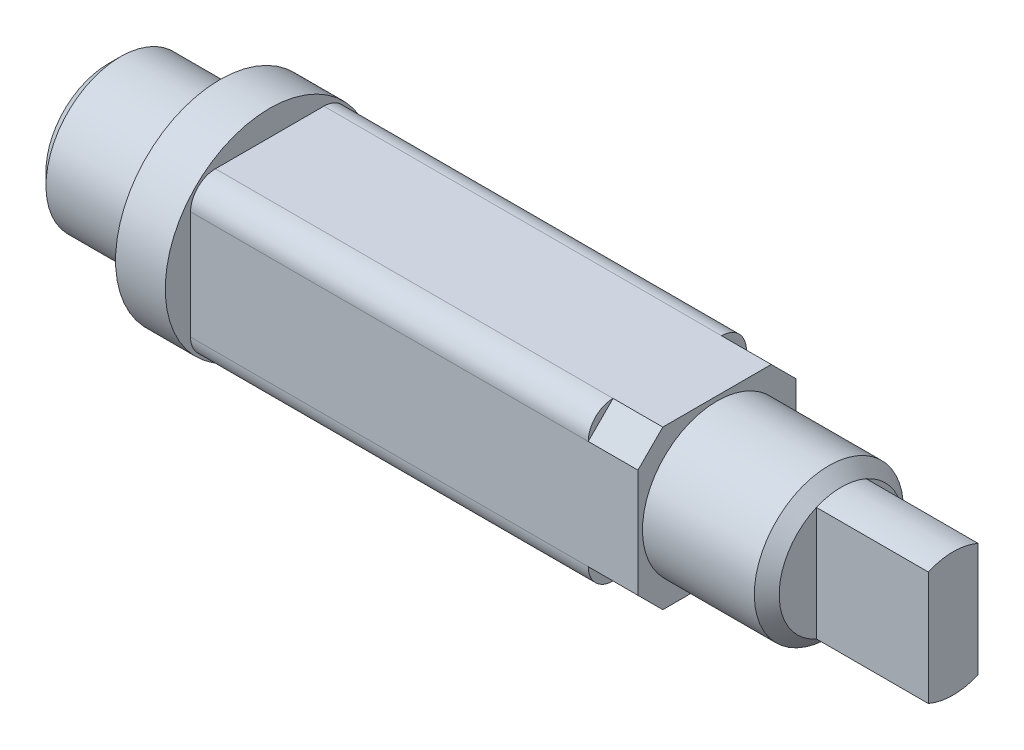
SolidWorks part; units mm, degrees
ref_plane "前视基准面" through (0, 0, 0) normal (0, 0, 1) x (1, 0, 0)
ref_plane "上视基准面" through (0, 0, 0) normal (0, 1, 0) x (1, 0, 0)
ref_plane "右视基准面" through (0, 0, 0) normal (1, 0, 0) x (0, 0, -1)
sketch "草图1" plane through (0, 0, 0) normal (0, 0, 1) x (1, 0, 0)
  line L0 (0, 3) -> (4, 3)
  line L1 (0, 3) -> (-0.5, 2.5)
  line L2 (4, 3) -> (4, 4.2)
  line L3 (4, 4.2) -> (6, 4.2)
  line L4 (6, 4.2) -> (6, 0)
  line L5 (6, 0) -> (0, 0)
  line L8 (-0.5, 2.5) -> (-0.5, 0)
  line L9 (-0.5, 0) -> (0, 0)
  point P10 (-0.5, 3)
revolve "旋转1" add sketch "草图1" angle 360 about L5
ref_plane "基准面1" through (6, 0, 0) normal (1, 0, 0) x (0, 0, -1)
sketch "草图2" plane through (6, 0, 0) normal (1, 0, 0) x (0, 0, -1)
  line L1 (-2.182, 3.182) -> (2.182, 3.182)
  line L2 (-3.182, 2.182) -> (-3.182, -2.182)
  line L3 (-2.182, -3.182) -> (2.182, -3.182)
  line L4 (3.182, 2.182) -> (3.182, -2.182)
  line L5 (-3.182, 3.182) -> (3.182, -3.182) construction
  line L6 (-3.182, -3.182) -> (3.182, 3.182) construction
  arc A0 (3.182, 2.182) -> (2.182, 3.182) centre (2.182, 2.182) ccw
  arc A1 (2.182, -3.182) -> (3.182, -2.182) centre (2.182, -2.182) ccw
  arc A2 (-3.182, -2.182) -> (-2.182, -3.182) centre (-2.182, -2.182) ccw
  arc A3 (-3.182, 2.182) -> (-2.182, 3.182) centre (-2.182, 2.182) cw
  point P0 (0, 0)
  dimension "D1" = 1
extrude "凸台-拉伸1" add sketch "草图2" along normal blind 16
ref_plane "基准面2" through (22, 0, 0) normal (1, 0, 0) x (0, 0, -1)
sketch "草图3" plane through (22, 0, 0) normal (1, 0, 0) x (0, 0, -1)
  line L0 (3.182, 2.182) -> (2.182, 3.182)
  line L1 (2.182, 3.182) -> (-2.182, 3.182)
  line L2 (3.182, 2.182) -> (3.182, -2.182)
  line L3 (2.182, -3.182) -> (-2.182, -3.182)
  line L4 (-3.182, 2.182) -> (-3.182, -2.182)
  line L5 (3.182, 3.182) -> (-3.182, -3.182) construction
  line L6 (3.182, -3.182) -> (-3.182, 3.182) construction
  line L7 (-2.182, 3.182) -> (-3.182, 2.182)
  line L8 (3.182, -2.182) -> (2.182, -3.182)
  line L9 (-2.182, -3.182) -> (-3.182, -2.182)
  point P0 (0, 0)
  point P10 (-3.182, 3.182)
extrude "凸台-拉伸2" add sketch "草图3" along normal blind 2
sketch "草图4" plane through (0, 0, 0) normal (0, 0, 1) x (1, 0, 0)
  line L0 (28.5, 3) -> (29, 2.5)
  line L1 (24, 3.182) -> (24, 2.182) construction
  line L2 (24, 3) -> (28.5, 3)
  line L3 (29, 2.5) -> (29, 0)
  line L4 (29, 0) -> (24, 0)
  line L5 (24, 2.182) -> (24, -2.182) construction
  line L6 (24, 0) -> (24, 3)
  point P6 (29, 3)
revolve "旋转2" add sketch "草图4" angle 360 about L4
ref_plane "基准面3" through (28.5, 0, 0) normal (1, 0, 0) x (0, 0, -1)
sketch "草图5" plane through (28.5, 0, 0) normal (1, 0, 0) x (0, 0, -1)
  line L0 (-1, -1.7913) -> (-1, -2.2913)
  line L1 (-1, 1.7913) -> (-1, 2.2913)
  line L2 (-1, 1.7913) -> (-1, -1.7913)
  line L3 (1, 1.7913) -> (1, 2.2913)
  line L4 (1, 1.7913) -> (1, -1.7913)
  line L5 (1, -1.7913) -> (1, -2.2913)
  circle A2 centre (0, 0) radius 2.5 construction
  arc A3 (-1, -2.2913) -> (1, -2.2913) centre (0, 0) ccw
  arc A4 (1, 2.2913) -> (-1, 2.2913) centre (0, 0) ccw
  point P0 (0, 0)
extrude "凸台-拉伸3" add sketch "草图5" along normal blind 5
